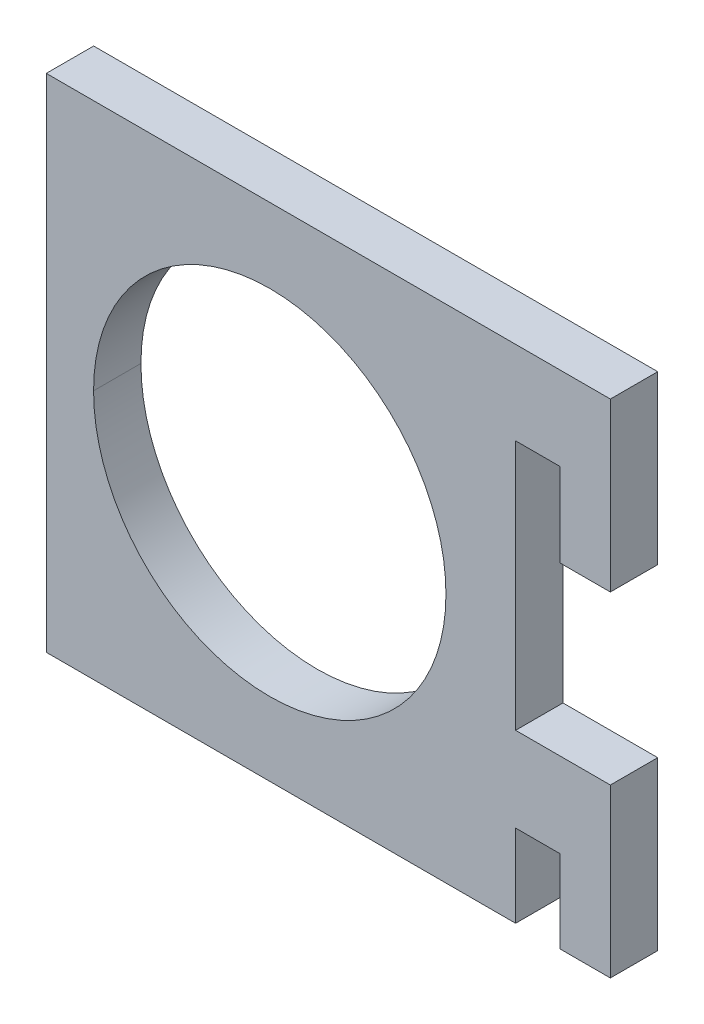
SolidWorks part; units mm, degrees
ref_plane "Front Plane" through (0, 0, 0) normal (0, 0, 1) x (1, 0, 0)
ref_plane "Top Plane" through (0, 0, 0) normal (0, 1, 0) x (1, 0, 0)
ref_plane "Right Plane" through (0, 0, 0) normal (1, 0, 0) x (0, 0, -1)
sketch "Sketch1" plane through (0, 0, 0) normal (0, 0, 1) x (1, 0, 0)
  line L1 (-38.6732, -24.0708) -> (18.4768, -24.0708)
  line L2 (-38.6732, -24.0708) -> (-38.6732, 26.7292)
  line L3 (-38.6732, 26.7292) -> (18.4768, 26.7292)
  line L4 (18.4768, -24.0708) -> (18.4768, 26.7292)
  dimension "D1" = 50.8
  dimension "D2" = 57.15
extrude "Boss-Extrude1" add sketch "Sketch1" along normal blind 4.8
sketch "Sketch3" plane through (0, 0, 4.8) normal (0, 0, 1) x (1, 0, 0)
  line L0 (18.4768, -24.0708) -> (18.4768, 26.7292) construction
  line L1 (18.4768, -7.1374) -> (8.8768, -7.1374)
  line L2 (18.4768, -7.1374) -> (18.4768, 9.7959)
  line L3 (18.4768, 9.7959) -> (8.8768, 9.7959)
  line L4 (8.8768, -7.1374) -> (8.8768, 9.7959)
  line L5 (18.4768, -7.1374) -> (8.8768, 9.7959) construction
  line L6 (18.4768, 9.7959) -> (8.8768, -7.1374) construction
  line L7 (18.4768, -24.0708) -> (18.4768, -7.1374)
  line L8 (-38.6732, -24.0708) -> (18.4768, -24.0708) construction
  line L9 (18.4768, 9.7959) -> (18.4768, 26.7292)
  point P4 (13.6768, 1.3292)
  line M9 (18.4768, -24.0708) -> (18.4768, 26.7292)
  dimension "D1" = 16.9333
  dimension "D2" = 9.6
extrude "Cut-Extrude2" cut sketch "Sketch3" against normal through all contours L4 L1 L3 M9
sketch "Sketch4" plane through (0, 0, 0) normal (0, 0, -1) x (-1, 0, 0)
  line L1 (-8.8768, 9.7959) -> (-13.3768, 9.7959)
  line L2 (-8.8768, 9.7959) -> (-8.8768, 18.2626)
  line L3 (-8.8768, 18.2626) -> (-13.3768, 18.2626)
  line L4 (-13.3768, 9.7959) -> (-13.3768, 18.2626)
  line L5 (-8.8768, 9.7959) -> (-13.3768, 18.2626) construction
  line L6 (-8.8768, 18.2626) -> (-13.3768, 9.7959) construction
  line L11 (-8.8768, -7.1374) -> (-8.8768, -24.0708) construction
  line L12 (38.6732, -24.0708) -> (-18.4768, -24.0708) construction
  line L15 (-8.8768, -24.0708) -> (-13.3768, -24.0708)
  line L16 (-8.8768, -24.0708) -> (-8.8768, -15.7134)
  line L17 (-8.8768, -15.7134) -> (-13.3768, -15.7134)
  line L18 (-13.3768, -24.0708) -> (-13.3768, -15.7134)
  line L19 (-8.8768, -24.0708) -> (-13.3768, -15.7134) construction
  line L20 (-8.8768, -15.7134) -> (-13.3768, -24.0708) construction
  point P4 (-11.1268, 14.0292)
  point P13 (-11.1268, -19.8921)
  line M9 (-18.4768, 9.7959) -> (-8.8768, 9.7959)
  line M13 (-18.4768, -24.0708) -> (38.6732, -24.0708)
  dimension "D1" = 4.5
  dimension "D2" = 8.4667
  dimension "D3" = 4.5
extrude "Cut-Extrude6" cut sketch "Sketch7" against normal through all contours A1
sketch "Sketch7" plane through (21.9693, 54.5942, 4.8) normal (0, 0, 1) x (0.8371, 0.5471, 0)
  line L16 (-50.2292, -61.1477) -> (-45.9601, -63.9378)
  line L26 (-45.9601, -63.9378) -> (-36.6961, -49.7633)
  line L32 (-27.4321, -35.5888) -> (-18.1681, -21.4144)
  line L33 (-18.1681, -21.4144) -> (-66.0069, 9.8517)
  line L34 (-66.0069, 9.8517) -> (-93.799, -32.6718)
  line L35 (-93.799, -32.6718) -> (-53.996, -58.6858)
  line L42 (-27.0691, -25.7115) -> (-31.7011, -32.7987)
  line L50 (-53.996, -58.6858) -> (-49.4238, -51.69)
  line L52 (-36.6961, -49.7633) -> (-44.732, -44.5113)
  line L57 (-30.836, -23.2496) -> (-27.0691, -25.7115)
  line L58 (-44.732, -44.5113) -> (-30.836, -23.2496)
  line L60 (-31.7011, -32.7987) -> (-27.4321, -35.5888)
  line L62 (-49.4238, -51.69) -> (-45.6569, -54.1519)
  line L64 (-45.6569, -54.1519) -> (-50.2292, -61.1477)
  circle A1 centre (-61.0093, -23.8889) radius 17.8492
extrude "Cut-Extrude7" cut sketch "Sketch4" against normal through all contours L4 L2 L3 M9 | L18 L16 L17 M13
extrude "Cut-Extrude8" cut sketch "Sketch8" against normal through all contours A2
sketch "Sketch8" plane through (21.9693, 54.7035, 0) normal (0, 0, -1) x (0, -1, 0)
  line L16 (44.9076, 8.5925) -> (36.4409, 8.5925)
  line L22 (78.7742, 3.4925) -> (78.7742, 8.5925)
  line L23 (36.4409, 8.5925) -> (36.4409, 13.0925)
  line L25 (44.9076, 3.4925) -> (44.9076, 8.5925)
  line L27 (36.4409, 13.0925) -> (61.8409, 13.0925)
  line L32 (78.7742, 13.0925) -> (78.7742, 60.6425)
  line L33 (78.7742, 60.6425) -> (27.9742, 60.6425)
  line L34 (27.9742, 60.6425) -> (27.9742, 3.4925)
  line L35 (27.9742, 3.4925) -> (44.9076, 3.4925)
  line L46 (70.4168, 13.0925) -> (78.7742, 13.0925)
  line L47 (61.8409, 13.0925) -> (61.8409, 3.4925)
  line L49 (61.8409, 3.4925) -> (78.7742, 3.4925)
  line L51 (78.7742, 8.5925) -> (70.4168, 8.5925)
  line L53 (70.4168, 8.5925) -> (70.4168, 13.0925)
  circle A2 centre (53.3742, 38.0001) radius 17.8492
equation "\"MDF\"= 4.8mm"
equation "\"Foamcore\"= 4.6mm"
equation "\"GMaterial\"= \"MDF\""
equation "\"D1@Boss-Extrude1\"=\"GMaterial\""
equation "\"PCB\" = 1.6mm"
equation "\"BaseWidth\" = 10in"
equation "\"SkidLength\" = 1in"
equation "\"SkidClearance\" = 0.4in"
equation "\"MotorMountLength\" = 2in"
equation "\"MotorMountWidth\" = \"GMaterial\""
equation "\"D1@Sketch1\"=\"MotorMountLength\""
equation "\"D2@Sketch1\"=\"MotorMountHeight\""
equation "\"MotorMountHeight\" = 2.25in"
equation "\"D2@Sketch3\"=\"GMaterial\"*2"
equation "\"D1@Sketch4\"=\"GMaterial\" - \"LaserCutterOffset\""
equation "\"UnoStackWidth\" = 77.4mm"
equation "\"UnoStackLength\" = 79.8mm"
equation "\"UnoStackHeight\" = 34.2mm"
equation "\"TallHexRiserHeight\" = 22.2mm"
equation "\"PingPongBallSize\" = 40mm"
equation "\"BarrelLength\" = 9in"
equation "\"BarrelSize\" = \"PingPongBallSize\""
equation "\"PlatformLength\" = 4in"
equation "\"PlatformWidth\" = 6in"
equation "\"WheelWidth\"= 26mm"
equation "\"WheelDiameter\"=2.99213"
equation "\"ServoMountHeight\"=2.49223"
equation "\"ServoGearHeight\" = 0.95330261in"
equation "\"ServoMountLength\"= 1.53774"
equation "\"PivotHoleRadius\"= 0.616358"
equation "\"PlatformMountHeight\" = 3.19"
equation "\"TensionOffSet\"= .3mm"
equation "\"MotorMountWedge\"=0.333333"
equation "\"LaserCutterOffset\"= .3mm"
equation "\"D3@Sketch4\"=\"GMaterial\"-\"LaserCutterOffset\""
